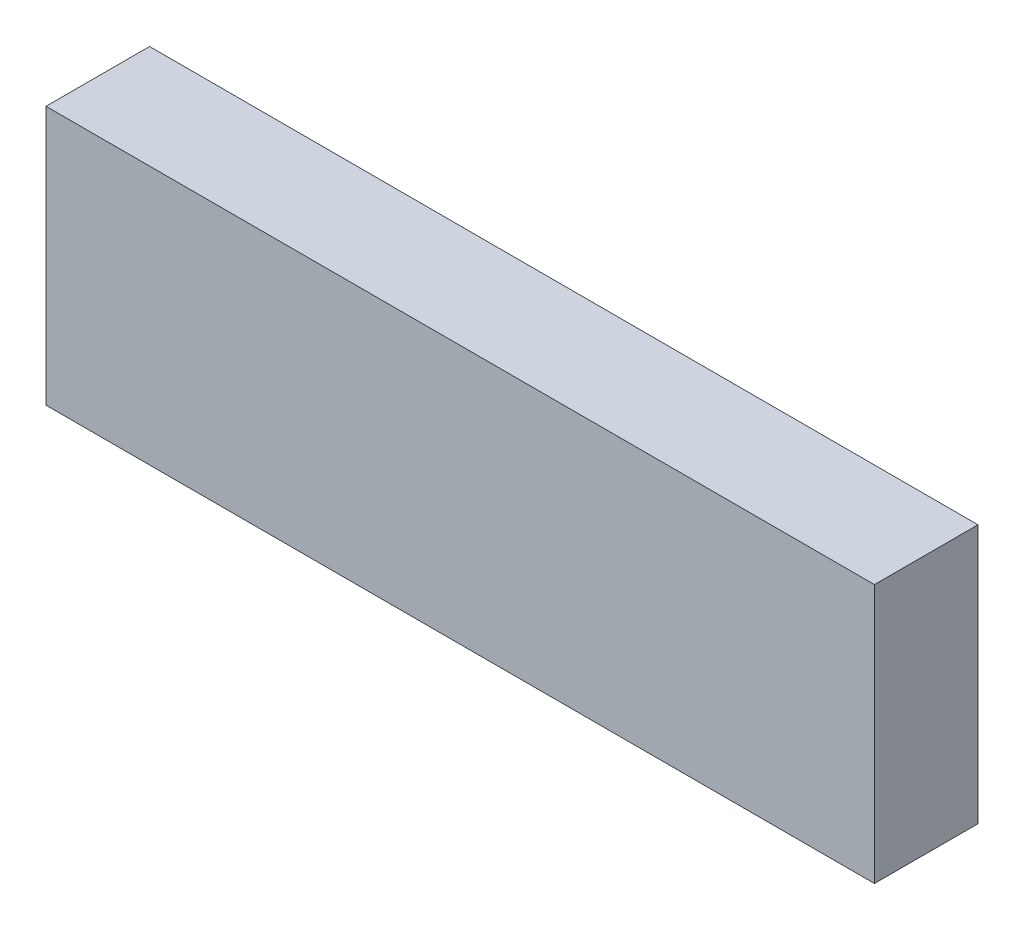
SolidWorks part; units mm, degrees
ref_plane "Front Plane" through (0, 0, 0) normal (0, 0, 1) x (1, 0, 0)
ref_plane "Top Plane" through (0, 0, 0) normal (0, 1, 0) x (1, 0, 0)
ref_plane "Right Plane" through (0, 0, 0) normal (1, 0, 0) x (0, 0, -1)
sketch "Sketch1" plane through (0, 0, 0) normal (0, 0, 1) x (1, 0, 0)
  line L1 (0, 0) -> (25.4, 0)
  line L2 (0, 0) -> (0, 7.9375)
  line L3 (0, 7.9375) -> (25.4, 7.9375)
  line L4 (25.4, 0) -> (25.4, 7.9375)
  dimension "D1" = 7.9375
  dimension "D2" = 25.4
extrude "Boss-Extrude1" add sketch "Sketch1" along normal blind 3.175
